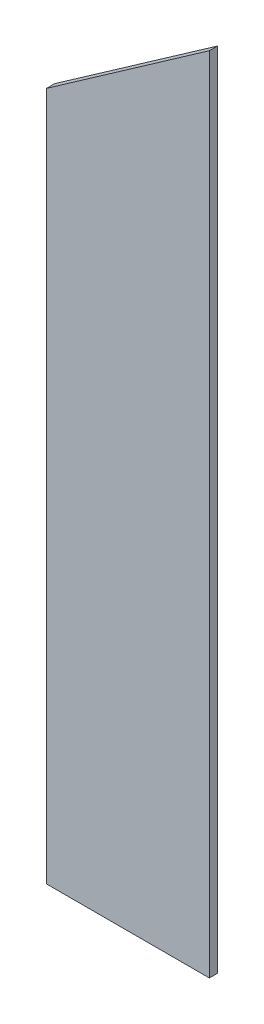
SolidWorks part; units mm, degrees
ref_plane "Front Plane" through (0, 0, 0) normal (0, 0, 1) x (1, 0, 0)
ref_plane "Top Plane" through (0, 0, 0) normal (0, 1, 0) x (1, 0, 0)
ref_plane "Right Plane" through (0, 0, 0) normal (1, 0, 0) x (0, 0, -1)
sketch "Sketch2" plane through (0, 0, 0) normal (0, 0, 1) x (1, 0, 0)
  line L0 (0, 0) -> (0, 571.8404) construction
  line L1 (-50, 422.98) -> (0, 422.98) construction
  line L2 (-50, 422.98) -> (-50, 0)
  line L3 (-50, 0) -> (50, 0)
  line L4 (50, 422.98) -> (50, 0)
  line L5 (-50, 422.98) -> (50, 493.0008)
  line L6 (50, 493.0008) -> (50, 422.98)
  line L7 (0, 422.98) -> (50, 422.98) construction
  dimension "D1" = 100
  dimension "D2" = 422.98
  dimension "D3" = 35
extrude "Boss-Extrude1" add sketch "Sketch2" along normal blind 5 contours L2 L3 L4 L6 L5
